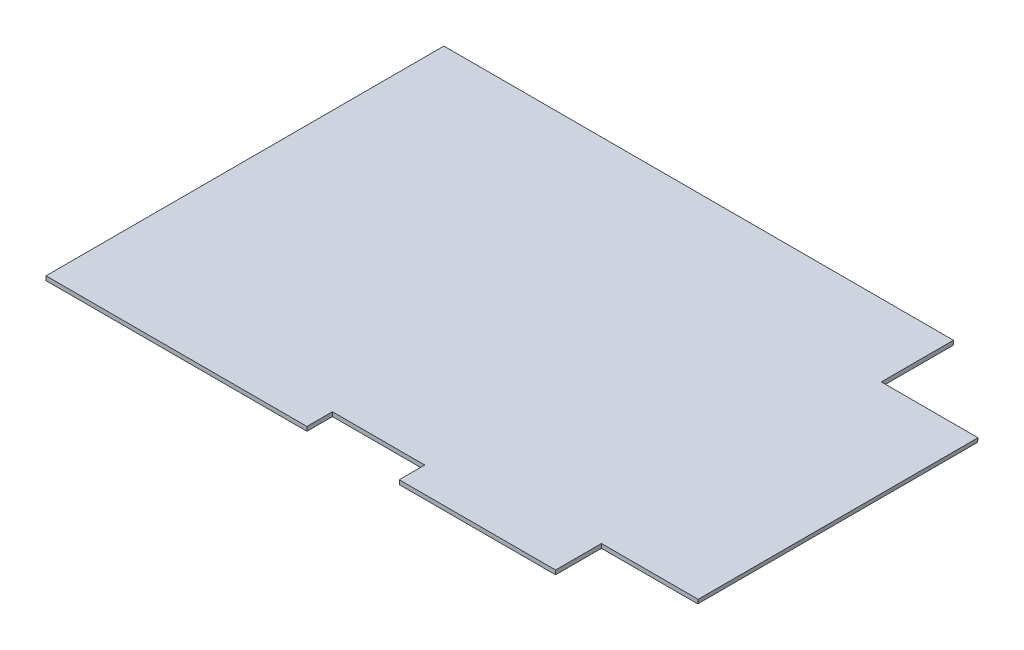
SolidWorks part; units mm, degrees
ref_plane "Alzado" through (0, 0, 0) normal (0, 0, 1) x (1, 0, 0)
ref_plane "Planta" through (0, 0, 0) normal (0, 1, 0) x (1, 0, 0)
ref_plane "Vista lateral" through (0, 0, 0) normal (1, 0, 0) x (0, 0, -1)
sketch "Croquis1" plane through (0, 0, 0) normal (0, 0, 1) x (1, 0, 0)
  line L10 (-53.8399, -4.6783) -> (-53.8399, -5.6411)
  line L12 (-68.5143, -4.6783) -> (73.5457, -4.6783)
  line L24 (51.0154, -4.6783) -> (73.5457, -4.6783)
  line L26 (-53.8399, -5.6411) -> (84.709, -5.6411)
  line L27 (84.709, -5.6411) -> (84.8047, -4.6783)
  line L28 (73.5457, -4.6783) -> (84.84, -4.6783)
  line L32 (-68.5143, -5.8159) -> (89.9101, -5.8159)
  line L33 (89.9101, -5.8159) -> (89.9101, -4.6783)
  line L34 (89.9101, -4.6783) -> (73.6154, -4.6783)
  line L35 (73.6154, -4.6783) -> (73.6154, -4.7636)
  line L36 (73.6154, -4.7636) -> (51.0154, -4.7636)
  line L37 (51.0154, -4.7636) -> (51.0154, -4.6783)
  line L38 (51.0154, -4.6783) -> (-68.5143, -4.6783)
  line L39 (-68.5143, -4.6783) -> (-68.5143, -5.8159)
  line L46 (51.0154, -4.6783) -> (-68.5143, -4.6783)
  line L61 (-68.5143, -4.6783) -> (-68.5143, -5.8159)
  dimension "D2" = 0.3
extrude "Saliente-Extruir1" add sketch "Croquis1" along normal blind 91 contours L28 L12 L10 L26 L27
sketch "Croquis3" plane through (0, -4.6783, 0) normal (0, 1, 0) x (1, 0, 0)
  line L0 (5.8322, -89.5) -> (5.8322, -85.1693) construction
  line L1 (26.9383, -89.5) -> (5.8322, -89.5)
  line L2 (26.9383, -89.5) -> (26.9383, -85.1693)
  line L3 (26.9383, -85.1693) -> (5.8322, -85.1693)
  line L4 (5.8322, -89.5) -> (5.8322, -85.1693)
  line L5 (5.8322, -85.1693) -> (26.9383, -85.1693) construction
  line L6 (-52, -2.5) -> (92.8154, -2.5) construction
  line L7 (62.6929, -2.5) -> (92.8154, -2.5)
  line L8 (62.6929, -2.5) -> (62.6929, -16.5)
  line L9 (62.6929, -16.5) -> (92.8154, -16.5)
  line L10 (92.8154, -2.5) -> (92.8154, -16.5)
  line L11 (92.8154, 2.5) -> (92.8154, -94.5) construction
  line L13 (92.8154, -94.5) -> (62.6929, -94.5)
  line L14 (92.8154, -94.5) -> (92.8154, -80.5)
  line L15 (92.8154, -80.5) -> (62.6929, -80.5)
  line L16 (62.6929, -94.5) -> (62.6929, -80.5)
  dimension "D1" = 14
  dimension "D2" = 14
extrude "Cortar-Extruir2" cut sketch "Croquis3" against normal blind 91
sketch "Croquis4" plane through (0, -4.6783, 0) normal (0, 1, 0) x (1, 0, 0)
  line L0 (62.6929, -2.5) -> (62.6929, 0)
  line L1 (-53.8399, 0) -> (84.8047, 0) construction
  line L2 (62.6929, 0) -> (84.8047, 0)
  line L3 (84.8047, 0) -> (84.8047, -2.5)
  line L4 (84.8047, -2.5) -> (62.6929, -2.5)
extrude "Cortar-Extruir3" cut sketch "Croquis4" against normal blind 10
sketch "Croquis5" plane through (0, -4.6783, 0) normal (0, 1, 0) x (1, 0, 0)
  line L0 (5.8322, -89.5) -> (5.8322, -91)
  line L1 (-53.8399, -91) -> (62.6929, -91) construction
  line L2 (5.8322, -91) -> (26.9505, -91)
  line L3 (26.9505, -91) -> (26.9383, -89.5)
  line L4 (5.8322, -89.5) -> (26.9383, -89.5) construction
  line L5 (26.9383, -89.5) -> (5.8322, -89.5)
extrude "Cortar-Extruir4" cut sketch "Croquis5" against normal blind 10
